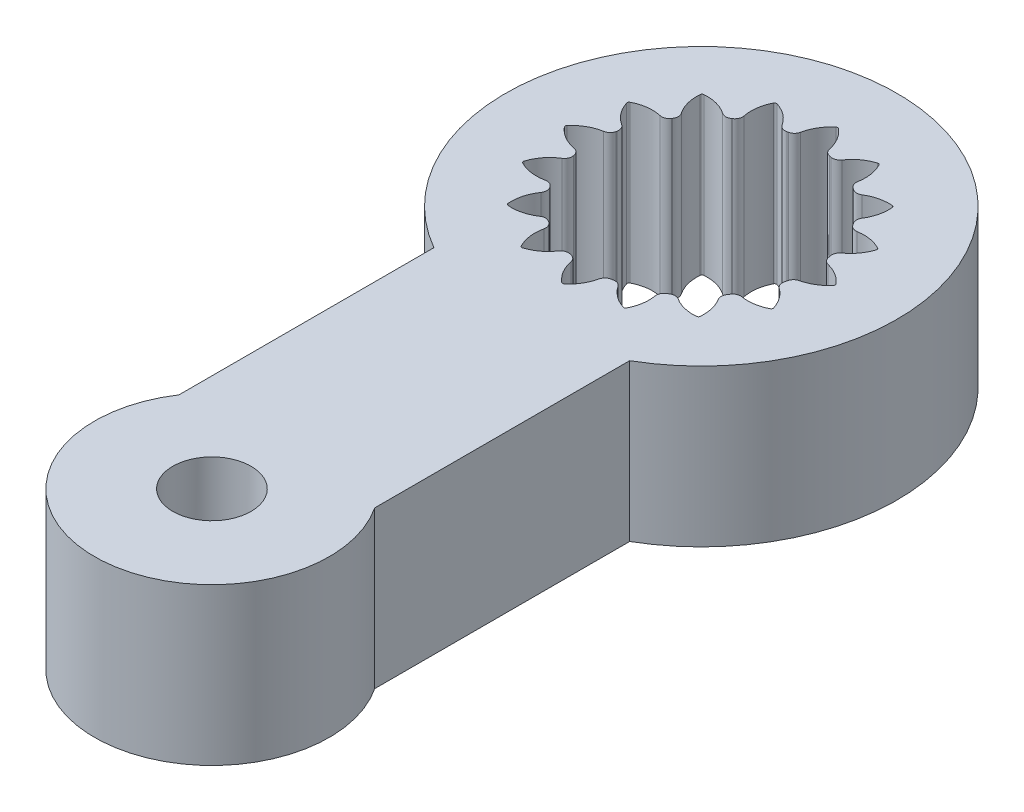
SolidWorks part; units mm, degrees
ref_plane "Ön Düzlem" through (0, 0, 0) normal (0, 0, 1) x (1, 0, 0)
ref_plane "Üst Düzlem" through (0, 0, 0) normal (0, 1, 0) x (1, 0, 0)
ref_plane "Sağ Düzlem" through (0, 0, 0) normal (1, 0, 0) x (0, 0, -1)
sketch "Sketch1" plane through (0, 0, 0) normal (0, 1, 0) x (1, 0, 0)
  circle A0 centre (0, 0) radius 5.6
  circle A1 centre (0, 0) radius 10
  dimension "D1" = 11.2
  dimension "D2" = 20
extrude "Boss-Extrude1" add sketch "Sketch1" along normal blind 8
sketch "Sketch2" plane through (0, 8, 0) normal (0, 1, 0) x (1, 0, 0)
  line L0 (0, 0) -> (0, 7) construction
  circle A0 centre (0, 0) radius 7 construction
  arc A1 (-0.0642, 6.9483) -> (-0.7394, 5.8129) centre (1.2207, 5.4158) ccw
  circle A2 centre (0, 0) radius 5.6 construction
  arc A3 (0.0642, 6.9483) -> (0.7394, 5.8129) centre (-1.2207, 5.4158) cw
  arc A4 (-0.0642, 6.9483) -> (0.0642, 6.9483) centre (0, 6.8717) cw
  arc A5 (2.7106, 6.3702) -> (2.9041, 5.0849) centre (0.937, 5.446) cw
  arc A6 (2.5919, 6.4194) -> (1.5467, 5.6479) centre (3.1926, 4.5117) ccw
  arc A7 (2.5919, 6.4194) -> (2.7106, 6.3702) centre (2.6219, 6.324) cw
  arc A8 (4.9343, 4.8233) -> (4.6311, 3.5773) centre (2.942, 4.6483) cw
  arc A9 (4.8434, 4.9142) -> (3.6015, 4.6135) centre (4.6684, 2.9219) ccw
  arc A10 (4.8434, 4.9142) -> (4.9343, 4.8233) centre (4.8347, 4.8146) cw
  arc A11 (6.3968, 2.5432) -> (5.6491, 1.5147) centre (4.4891, 3.1439) cw
  arc A12 (6.3476, 2.6619) -> (5.103, 2.8624) centre (5.4234, 0.8883) ccw
  arc A13 (6.3476, 2.6619) -> (6.3968, 2.5432) centre (6.3014, 2.5733) cw
  arc A14 (6.8753, -0.123) -> (5.7934, -0.7865) centre (5.3428, 1.162) cw
  arc A15 (6.8753, 0.0055) -> (5.8128, 0.6645) centre (5.3428, -1.2795) ccw
  arc A16 (6.8753, 0.0055) -> (6.8753, -0.123) centre (6.7987, -0.0587) cw
  arc A17 (6.2972, -2.7693) -> (5.0371, -2.9672) centre (5.373, -0.9957) cw
  arc A18 (6.3464, -2.6506) -> (5.6185, -1.6364) centre (4.4387, -3.2513) ccw
  arc A19 (6.3464, -2.6506) -> (6.2972, -2.7693) centre (6.251, -2.6807) cw
  arc A20 (4.7503, -4.993) -> (3.4978, -4.6856) centre (4.5752, -3.0007) cw
  arc A21 (4.8412, -4.9022) -> (4.5531, -3.6805) centre (2.8488, -4.7271) ccw
  arc A22 (4.8412, -4.9022) -> (4.7503, -4.993) centre (4.7416, -4.8934) cw
  arc A23 (2.4702, -6.4555) -> (1.4188, -5.675) centre (3.0709, -4.5478) cw
  arc A24 (2.5889, -6.4063) -> (2.7879, -5.1524) centre (0.8153, -5.4821) ccw
  arc A25 (2.5889, -6.4063) -> (2.4702, -6.4555) centre (2.5003, -6.3601) cw
  arc A26 (-0.196, -6.934) -> (-0.8733, -5.7877) centre (1.089, -5.4015) cw
  arc A27 (-0.0675, -6.934) -> (0.6008, -5.8315) centre (-1.3525, -5.4015) ccw
  arc A28 (-0.0675, -6.934) -> (-0.196, -6.934) centre (-0.1317, -6.8574) cw
  arc A29 (-2.8423, -6.3559) -> (-3.0249, -5.0157) centre (-1.0687, -5.4317) cw
  arc A30 (-2.7236, -6.4051) -> (-1.6712, -5.6232) centre (-3.3243, -4.4974) ccw
  arc A31 (-2.7236, -6.4051) -> (-2.8423, -6.3559) centre (-2.7537, -6.3097) cw
  arc A32 (-5.066, -4.809) -> (-4.7116, -3.4863) centre (-3.0737, -4.634) cw
  arc A33 (-4.9752, -4.8999) -> (-3.6854, -4.5681) centre (-4.8001, -2.9076) ccw
  arc A34 (-4.9752, -4.8999) -> (-5.066, -4.809) centre (-4.9664, -4.8003) cw
  arc A35 (-6.5285, -2.5289) -> (-5.6857, -1.4367) centre (-4.6208, -3.1296) cw
  arc A36 (-6.4793, -2.6476) -> (-5.1435, -2.8311) centre (-5.5551, -0.874) ccw
  arc A37 (-6.4793, -2.6476) -> (-6.5285, -2.5289) centre (-6.4331, -2.559) cw
  arc A38 (-7.0071, 0.1373) -> (-5.8082, 0.8242) centre (-5.4745, -1.1477) cw
  arc A39 (-7.0071, 0.0088) -> (-5.8326, -0.6739) centre (-5.4745, 1.2938) ccw
  arc A40 (-7.0071, 0.0088) -> (-7.0071, 0.1373) centre (-6.9304, 0.073) cw
  arc A41 (-6.4289, 2.7836) -> (-5.0649, 2.961) centre (-5.5047, 1.01) cw
  arc A42 (-6.4781, 2.6649) -> (-5.6525, 1.5836) centre (-4.5704, 3.2656) ccw
  arc A43 (-6.4781, 2.6649) -> (-6.4289, 2.7836) centre (-6.3827, 2.695) cw
  arc A44 (-4.882, 5.0073) -> (-3.5658, 4.6575) centre (-4.707, 3.015) cw
  arc A45 (-4.9729, 4.9165) -> (-4.6278, 3.6071) centre (-2.9806, 4.7414) ccw
  arc A46 (-4.9729, 4.9165) -> (-4.882, 5.0073) centre (-4.8733, 4.9077) cw
  arc A47 (-2.6019, 6.4698) -> (-1.5309, 5.6599) centre (-3.2026, 4.5621) cw
  arc A48 (-2.7207, 6.4206) -> (-2.9059, 5.0932) centre (-0.947, 5.4964) ccw
  arc A49 (-2.7207, 6.4206) -> (-2.6019, 6.4698) centre (-2.632, 6.3744) cw
  arc A50 (-1.056, 5.4995) -> (-1.1167, 5.4875) centre (0, 0) ccw
  arc A51 (-3.0778, 4.6783) -> (-3.1151, 4.6536) centre (0, 0) ccw
  arc A52 (-4.6267, 3.1549) -> (-4.6451, 3.1278) centre (0, 0) ccw
  arc A53 (-5.4777, 1.1641) -> (-5.4833, 1.1374) centre (0, 0) ccw
  arc A54 (-5.5107, -0.9963) -> (-5.5054, -1.0249) centre (0, 0) ccw
  arc A55 (-4.7237, -3.0077) -> (-4.7033, -3.0396) centre (0, 0) ccw
  arc A56 (-3.2316, -4.5735) -> (-3.1884, -4.6037) centre (0, 0) ccw
  arc A57 (-1.2512, -5.4584) -> (-1.1814, -5.474) centre (0, 0) ccw
  arc A58 (0.9253, -5.523) -> (1.0158, -5.5071) centre (0, 0) ccw
  arc A59 (2.9703, -4.7474) -> (3.0634, -4.6878) centre (0, 0) ccw
  arc A60 (4.5677, -3.2397) -> (4.6386, -3.1375) centre (0, 0) ccw
  arc A61 (5.4642, -1.2258) -> (5.4913, -1.0978) centre (0, 0) ccw
  arc A62 (5.513, 0.9831) -> (5.489, 1.1095) centre (0, 0) ccw
  arc A63 (4.7029, 3.0401) -> (4.6376, 3.1389) centre (0, 0) ccw
  arc A64 (3.1622, 4.6217) -> (3.0777, 4.6785) centre (0, 0) ccw
  arc A65 (1.1364, 5.4835) -> (1.056, 5.4995) centre (0, 0) ccw
  arc A66 (-1.056, 5.4995) -> (-0.7394, 5.8129) centre (-1.1315, 5.8924) ccw
  arc A67 (-1.1167, 5.4875) -> (-1.5309, 5.6599) centre (-1.1965, 5.8795) cw
  arc A68 (-3.0778, 4.6783) -> (-2.9059, 5.0932) centre (-3.2977, 5.0125) ccw
  arc A69 (-3.1151, 4.6536) -> (-3.5658, 4.6575) centre (-3.3376, 4.986) cw
  arc A70 (-4.6451, 3.1278) -> (-5.0649, 2.961) centre (-4.9769, 3.3512) cw
  arc A71 (-4.6267, 3.1549) -> (-4.6278, 3.6071) centre (-4.9572, 3.3802) ccw
  arc A72 (-5.4777, 1.1641) -> (-5.6525, 1.5836) centre (-5.8689, 1.2472) ccw
  arc A73 (-5.4833, 1.1374) -> (-5.8082, 0.8242) centre (-5.8749, 1.2186) cw
  arc A74 (-5.5107, -0.9963) -> (-5.8326, -0.6739) centre (-5.9043, -1.0674) ccw
  arc A75 (-5.6857, -1.4367) -> (-5.5054, -1.0249) centre (-5.8987, -1.0981) ccw
  arc A76 (-4.7033, -3.0396) -> (-4.7116, -3.4863) centre (-5.0392, -3.2567) cw
  arc A77 (-4.7237, -3.0077) -> (-5.1435, -2.8311) centre (-5.0611, -3.2226) ccw
  arc A78 (-3.2316, -4.5735) -> (-3.6854, -4.5681) centre (-3.4624, -4.9002) ccw
  arc A79 (-3.0249, -5.0157) -> (-3.1884, -4.6037) centre (-3.4162, -4.9325) ccw
  arc A80 (-1.2512, -5.4584) -> (-1.6712, -5.6232) centre (-1.3406, -5.8483) ccw
  arc A81 (-0.8733, -5.7877) -> (-1.1814, -5.474) centre (-1.2658, -5.865) ccw
  arc A82 (0.9253, -5.523) -> (0.6008, -5.8315) centre (0.9914, -5.9175) ccw
  arc A83 (1.0158, -5.5071) -> (1.4188, -5.675) centre (1.0884, -5.9005) cw
  arc A84 (2.9703, -4.7474) -> (2.7879, -5.1524) centre (3.1824, -5.0865) ccw
  arc A85 (3.0634, -4.6878) -> (3.4978, -4.6856) centre (3.2823, -5.0226) cw
  arc A86 (4.5677, -3.2397) -> (4.5531, -3.6805) centre (4.894, -3.4711) ccw
  arc A87 (4.6386, -3.1375) -> (5.0371, -2.9672) centre (4.9699, -3.3616) cw
  arc A88 (5.4642, -1.2258) -> (5.6185, -1.6364) centre (5.8545, -1.3134) ccw
  arc A89 (5.4913, -1.0978) -> (5.7934, -0.7865) centre (5.8836, -1.1762) cw
  arc A90 (5.513, 0.9831) -> (5.8128, 0.6645) centre (5.9068, 1.0533) ccw
  arc A91 (5.489, 1.1095) -> (5.6491, 1.5147) centre (5.881, 1.1888) cw
  arc A92 (4.7029, 3.0401) -> (5.103, 2.8624) centre (5.0389, 3.2573) ccw
  arc A93 (4.6376, 3.1389) -> (4.6311, 3.5773) centre (4.9689, 3.3631) cw
  arc A94 (3.1622, 4.6217) -> (3.6015, 4.6135) centre (3.3881, 4.9518) ccw
  arc A95 (3.0777, 4.6785) -> (2.9041, 5.0849) centre (3.2975, 5.0126) cw
  arc A96 (1.1364, 5.4835) -> (1.5467, 5.6479) centre (1.2175, 5.8752) ccw
  arc A97 (1.056, 5.4995) -> (0.7394, 5.8129) centre (1.1315, 5.8924) cw
  circle A98 centre (0, 0) radius 5.6
  point P15 (-0.775, 5.5461)
  point P121 (-0.0659, 0.0071)
  point P132 (-4.4562, 3.3914)
  point P185 (0.775, 5.5461)
  circle M50 centre (0, 0) radius 5.6
  dimension "D1" = 14
  dimension "D3" = 2
  dimension "D4" = 0.1
  dimension "D6" = 0.4
  dimension "D2" = 1.55
  dimension "D5" = 16
extrude "Cut-Extrude1" cut sketch "Sketch2" against normal blind 8 contours A71 A69 A44 A46 A45 M50 | A68 A67 A47 A49 A48 M50
sketch "Sketch3" plane through (0, 8, 0) normal (0, 1, 0) x (1, 0, 0)
  line L0 (0, 0) -> (0, -25) construction
  line L1 (-5, -8.6603) -> (-5, -21.6834)
  line L2 (5, -8.6603) -> (5, -21.6834)
  arc A0 (-5, -21.6834) -> (5, -21.6834) centre (0, -25) ccw
  circle A1 centre (0, 0) radius 10 construction
  arc A2 (-5, -8.6603) -> (5, -8.6603) centre (0, 0) ccw
  circle A3 centre (0, -25) radius 2
  dimension "D2" = 12
  dimension "D4" = 4
  dimension "D5" = 10
  dimension "D1" = 25
  dimension "D3" = 5
extrude "Boss-Extrude2" add sketch "Sketch3" against normal blind 8
sketch "Sketch4" plane through (0, 0, 0) normal (0, -1, 0) x (1, 0, 0)
  line L1 (1.5011, 27.6) -> (-1.5011, 27.6)
  line L2 (-1.5011, 27.6) -> (-3.0022, 25)
  line L3 (-3.0022, 25) -> (-1.5011, 22.4)
  line L4 (-1.5011, 22.4) -> (1.5011, 22.4)
  line L5 (1.5011, 22.4) -> (3.0022, 25)
  line L6 (3.0022, 25) -> (1.5011, 27.6)
  circle A0 centre (0, 25) radius 2.6 construction
  dimension "D1" = 5.2
extrude "Cut-Extrude2" cut sketch "Sketch4" against normal blind 5
